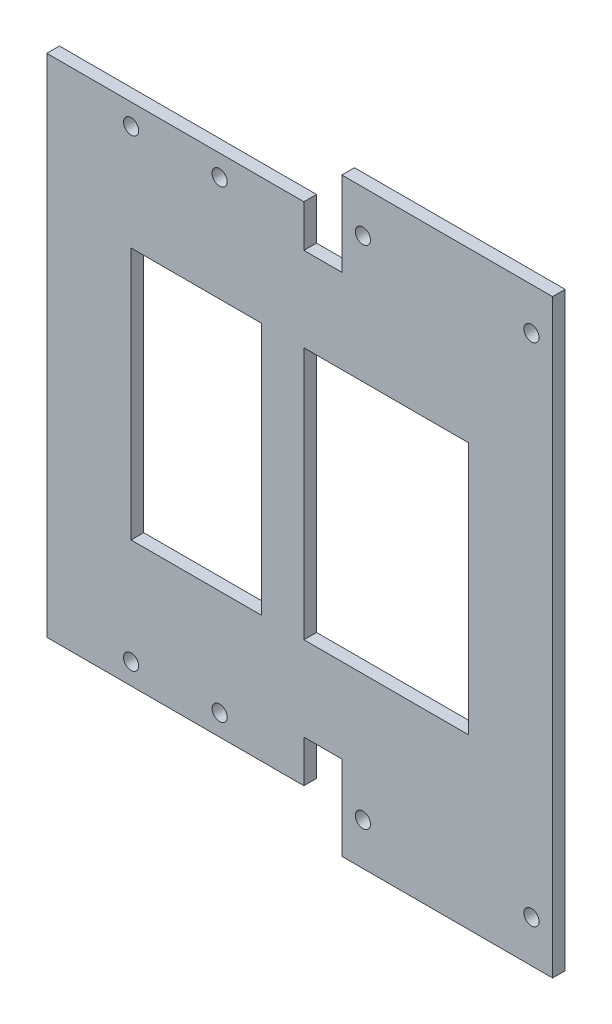
SolidWorks part; units mm, degrees
ref_plane "Plan de face" through (0, 0, 0) normal (0, 0, 1) x (1, 0, 0)
ref_plane "Plan de dessus" through (0, 0, 0) normal (0, 1, 0) x (1, 0, 0)
ref_plane "Plan de droite" through (0, 0, 0) normal (1, 0, 0) x (0, 0, -1)
sketch "Esquisse1" plane through (0, 0, 0) normal (0, 0, 1) x (1, 0, 0)
  line L0 (0, 0) -> (120, 0)
  line L1 (0, 0) -> (0, 100)
  line L2 (120, 0) -> (120, 100)
  line L3 (0, 100) -> (120, 100)
  line L4 (0, 100) -> (0, 110)
  line L5 (0, 100) -> (61, 100)
  line L6 (0, 110) -> (61, 110)
  line L7 (61, 100) -> (61, 110)
  line L8 (0, 0) -> (0, -10)
  line L9 (0, 0) -> (61, 0)
  line L10 (0, -10) -> (61, -10)
  line L11 (61, 0) -> (61, -10)
  line L12 (120, 100) -> (120, 120)
  line L13 (120, 100) -> (70, 100)
  line L14 (120, 120) -> (70, 120)
  line L15 (70, 100) -> (70, 120)
  line L16 (120, 0) -> (120, -20)
  line L17 (120, 0) -> (70, 0)
  line L18 (120, -20) -> (70, -20)
  line L19 (70, 0) -> (70, -20)
  line L20 (20, 20) -> (51, 20)
  line L21 (20, 20) -> (20, 80)
  line L22 (51, 20) -> (51, 80)
  line L23 (20, 80) -> (51, 80)
  line L24 (100, 20) -> (61, 20)
  line L25 (100, 20) -> (100, 80)
  line L26 (61, 20) -> (61, 80)
  line L27 (100, 80) -> (61, 80)
  circle A0 centre (20, 105) radius 1.8
  circle A1 centre (41, 105) radius 1.8
  circle A2 centre (20, -5) radius 1.8
  circle A3 centre (41, -5) radius 1.8
  circle A4 centre (75, -10) radius 1.8
  circle A5 centre (115, -10) radius 1.8
  circle A6 centre (75, 110) radius 1.8
  circle A7 centre (115, 110) radius 1.8
  dimension "D18" = 3.6
  dimension "D19" = 3.6
  dimension "D20" = 3.6
  dimension "D21" = 3.6
  dimension "D25" = 3.6
  dimension "D26" = 3.6
  dimension "D30" = 3.6
  dimension "D31" = 3.6
  dimension "D1" = 120
  dimension "D2" = 100
  dimension "D3" = 61
  dimension "D4" = 61
  dimension "D5" = 50
  dimension "D6" = 50
  dimension "D7" = 10
  dimension "D8" = 10
  dimension "D9" = 20
  dimension "D10" = 20
  dimension "D11" = 10
  dimension "D12" = 20
  dimension "D13" = 20
  dimension "D14" = 20
  dimension "D15" = 20
  dimension "D16" = 20
  dimension "D17" = 31
  dimension "D22" = 5
  dimension "D23" = 5
  dimension "D24" = 20
  dimension "D27" = 20
  dimension "D28" = 5
  dimension "D29" = 5
  dimension "D32" = 20
  dimension "D33" = 5
  dimension "D34" = 5
  dimension "D35" = 20
  dimension "D36" = 5
  dimension "D37" = 5
  dimension "D38" = 10
  dimension "D39" = 10
  dimension "D40" = 10
  dimension "D41" = 10
extrude "Boss.-Extru.1" add sketch "Esquisse1" along normal blind 3 contours L3 L1 L0 L2 L27 L25 L24 L26 L21 L23 L22 L20 | L0 L19 L18 L16 A5 A4 | L11 L0 L8 L10 A3 A2 | L3 L7 L6 L4 A1 A0 | L15 L3 L12 L14 A7 A6
